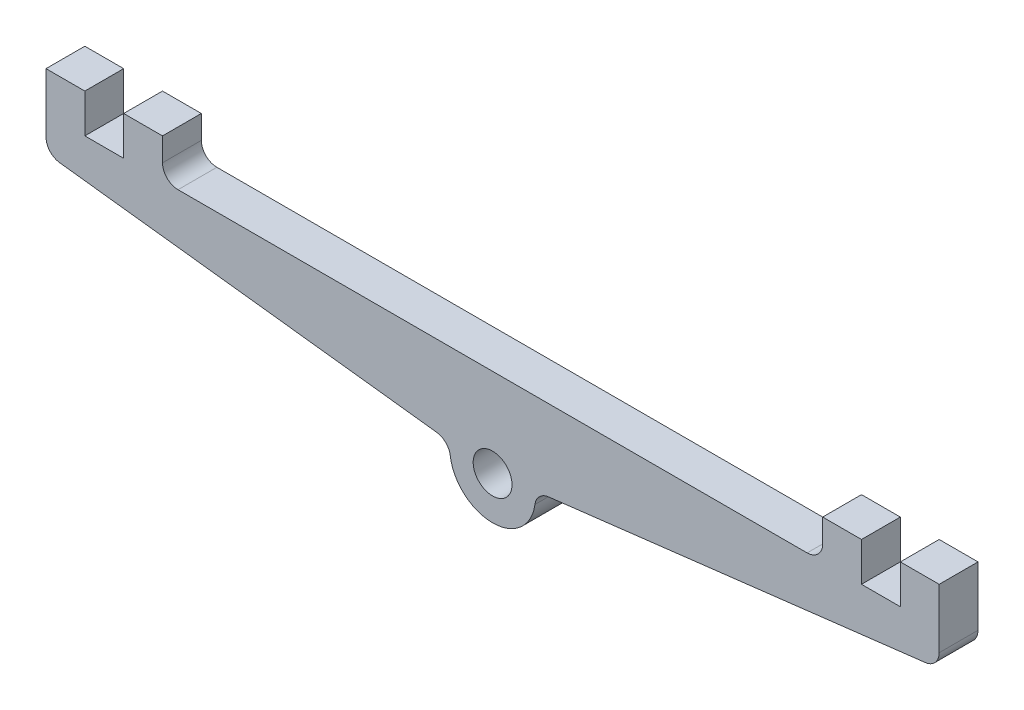
SolidWorks part; units mm, degrees
ref_plane "Front Plane" through (0, 0, 0) normal (0, 0, 1) x (1, 0, 0)
ref_plane "Top Plane" through (0, 0, 0) normal (0, 1, 0) x (1, 0, 0)
ref_plane "Right Plane" through (0, 0, 0) normal (1, 0, 0) x (0, 0, -1)
sketch "Sketch1" plane through (0, 0, 0) normal (0, 0, 1) x (1, 0, 0)
  line L0 (-66.675, 8.128) -> (-9.1415, 1.269)
  line L1 (-66.675, 14.478) -> (-60.325, 14.478)
  line L2 (-66.675, 14.478) -> (-66.675, 8.128) construction
  line L3 (0, 0) -> (0, 14.478) construction
  line L4 (0, 0) -> (0, -6.985) construction
  line L5 (66.675, 14.478) -> (66.675, 8.128) construction
  line L6 (66.675, 8.128) -> (9.1415, 1.269)
  line L7 (0, -6.985) -> (0, -10.922) construction
  line L8 (-73.025, 11.1402) -> (-73.025, 20.828)
  line L9 (-66.675, 8.128) -> (-70.7857, 8.6181)
  line L10 (-66.675, 14.478) -> (-66.675, 20.828)
  line L11 (-66.675, 20.828) -> (-73.025, 20.828)
  line L12 (-60.325, 14.478) -> (-60.325, 20.828)
  line L13 (-60.325, 20.828) -> (-53.975, 20.828)
  line L14 (-53.975, 20.828) -> (-53.975, 17.018)
  line L15 (-51.435, 14.478) -> (51.435, 14.478)
  line L16 (66.675, 8.128) -> (70.7857, 8.6181)
  line L17 (73.025, 11.1402) -> (73.025, 20.828)
  line L18 (66.675, 20.828) -> (73.025, 20.828)
  line L19 (66.675, 14.478) -> (66.675, 20.828)
  line L20 (66.675, 14.478) -> (60.325, 14.478)
  line L21 (60.325, 14.478) -> (60.325, 20.828)
  line L22 (60.325, 20.828) -> (53.975, 20.828)
  line L23 (53.975, 20.828) -> (53.975, 17.018)
  circle A0 centre (0, 0) radius 3.175
  arc A1 (-6.9243, -0.919) -> (6.9243, -0.919) centre (0, 0) ccw
  arc A2 (-9.1415, 1.269) -> (-6.9243, -0.919) centre (-9.4422, -1.2531) cw
  arc A3 (9.1415, 1.269) -> (6.9243, -0.919) centre (9.4422, -1.2531) ccw
  circle A4 centre (0, 0) radius 10.922 construction
  arc A5 (-73.025, 11.1402) -> (-70.7857, 8.6181) centre (-70.485, 11.1402) ccw
  arc A6 (-51.435, 14.478) -> (-53.975, 17.018) centre (-51.435, 17.018) cw
  arc A7 (73.025, 11.1402) -> (70.7857, 8.6181) centre (70.485, 11.1402) cw
  arc A8 (51.435, 14.478) -> (53.975, 17.018) centre (51.435, 17.018) ccw
  dimension "D1" = 6.35
  dimension "D4" = 25.4
  dimension "D5" = 6.985
  dimension "D6" = 2.54
  dimension "D8" = 21.844
  dimension "D9" = 2.54
  dimension "D14" = 2.54
  dimension "D2" = 6.35
  dimension "D3" = 133.35
  dimension "D7" = 83.201
  dimension "D10" = 6.35
  dimension "D11" = 6.35
  dimension "D12" = 6.35
  dimension "D13" = 6.35
extrude "Extrude1" add sketch "Sketch1" along normal blind 6.35
